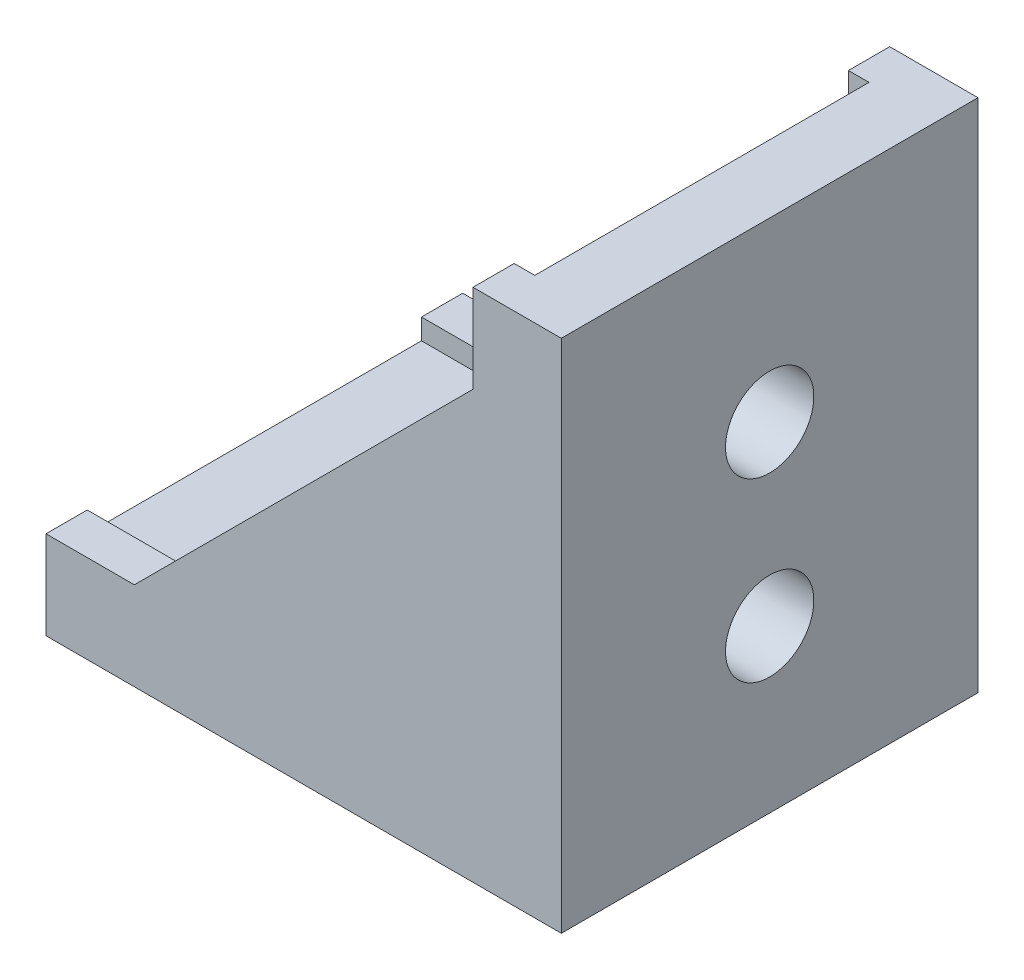
SolidWorks part; units mm, degrees
ref_plane "前视基准面" through (0, 0, 0) normal (0, 0, 1) x (1, 0, 0)
ref_plane "上视基准面" through (0, 0, 0) normal (0, 1, 0) x (1, 0, 0)
ref_plane "右视基准面" through (0, 0, 0) normal (1, 0, 0) x (0, 0, -1)
other "Configuration Table"
sketch "草图1" plane through (0, 0, 0) normal (0, 0, 1) x (1, 0, 0)
  line L0 (0, 0) -> (35, 0)
  line L1 (35, 0) -> (35, 35)
  line L2 (35, 35) -> (29, 35)
  line L3 (29, 35) -> (29, 29)
  line L4 (29, 29) -> (6, 6)
  line L5 (6, 6) -> (0, 6)
  line L6 (0, 6) -> (0, 0)
  dimension "D1" = 35
  dimension "D2" = 6
  dimension "D3" = 6
extrude "凸台-拉伸1" add sketch "草图1" along normal mid plane 28.3
sketch "草图2" plane through (0, 0, 0) normal (0, 0, 1) x (1, 0, 0)
  line L0 (0, 4.6) -> (30.4, 4.6)
  line L1 (0, 6) -> (0, 0) construction
  line L2 (30.4, 4.6) -> (30.4, 35)
  line L3 (35, 35) -> (29, 35) construction
  line L4 (30.4, 35) -> (0, 35)
  line L5 (0, 35) -> (0, 4.6)
  line L6 (35, 0) -> (35, 35) construction
  dimension "D1" = 4.6
extrude "切除-拉伸1" cut sketch "草图2" along normal mid plane 22.7
sketch "草图4" plane through (0, 0, 0) normal (0, 1, 0) x (1, 0, 0)
  line L0 (-5.3812, 0) -> (45.3159, 0) construction
  line L3 (35, -14.15) -> (35, 14.15) construction
  circle A2 centre (23, 0) radius 3
  circle A3 centre (11, 0) radius 3
  point P7 (0, 0)
  point P9 (0, 0)
  point P10 (35, 0.896)
  dimension "D1" = 6
  dimension "D2" = 6
  dimension "D3" = 24
  dimension "D4" = 12
extrude "切除-拉伸2" cut sketch "草图4" along normal up to next
sketch "草图5" plane through (0, 0, 0) normal (1, 0, 0) x (0, 0, -1)
  line L0 (0, 44.9599) -> (0, -4.5954) construction
  line L4 (-14.15, 35) -> (14.15, 35) construction
  circle A2 centre (0, 23) radius 3
  circle A3 centre (0, 11) radius 3
  point P10 (0, 0)
  point P11 (1.5078, 23)
  dimension "D1" = 6
  dimension "D2" = 6
  dimension "D3" = 12
  dimension "D4" = 12
extrude "切除-拉伸3" cut sketch "草图5" along normal up to next
